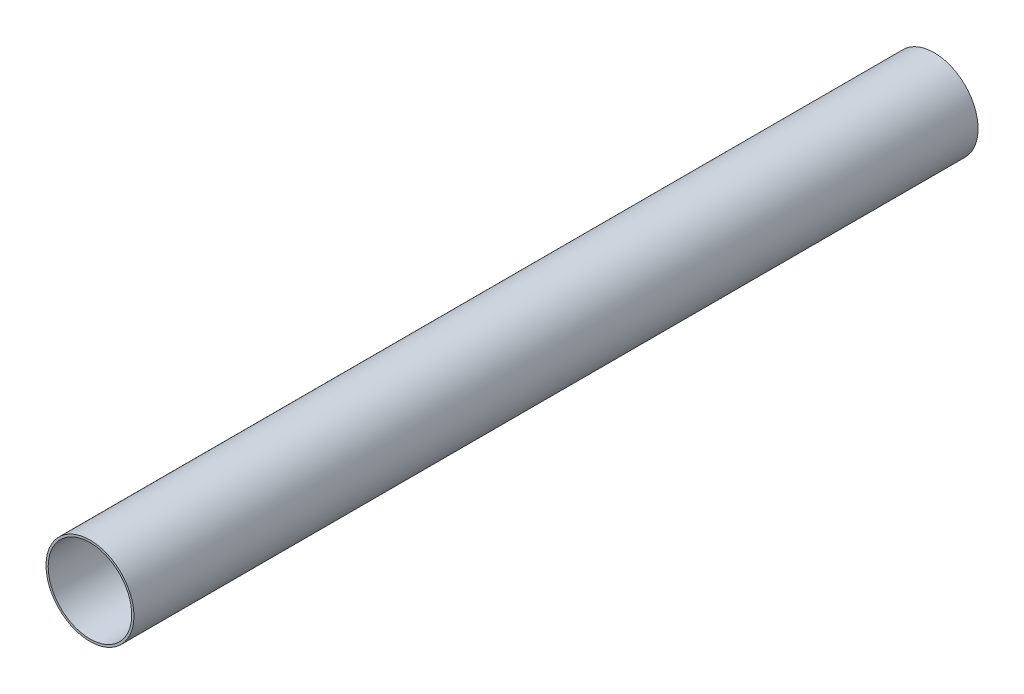
SolidWorks part; units mm, degrees
ref_plane "Front Plane" through (0, 0, 0) normal (0, 0, 1) x (1, 0, 0)
ref_plane "Top Plane" through (0, 0, 0) normal (0, 1, 0) x (1, 0, 0)
ref_plane "Right Plane" through (0, 0, 0) normal (1, 0, 0) x (0, 0, -1)
sketch "Sketch1" plane through (0, 0, 0) normal (0, 0, 1) x (1, 0, 0)
  circle A0 centre (0, 0) radius 31.75
  circle A1 centre (0, 0) radius 30.1625
  dimension "D1" = 63.5
  dimension "D2" = 60.325
extrude "Boss-Extrude1" add sketch "Sketch1" along normal blind 609.6
